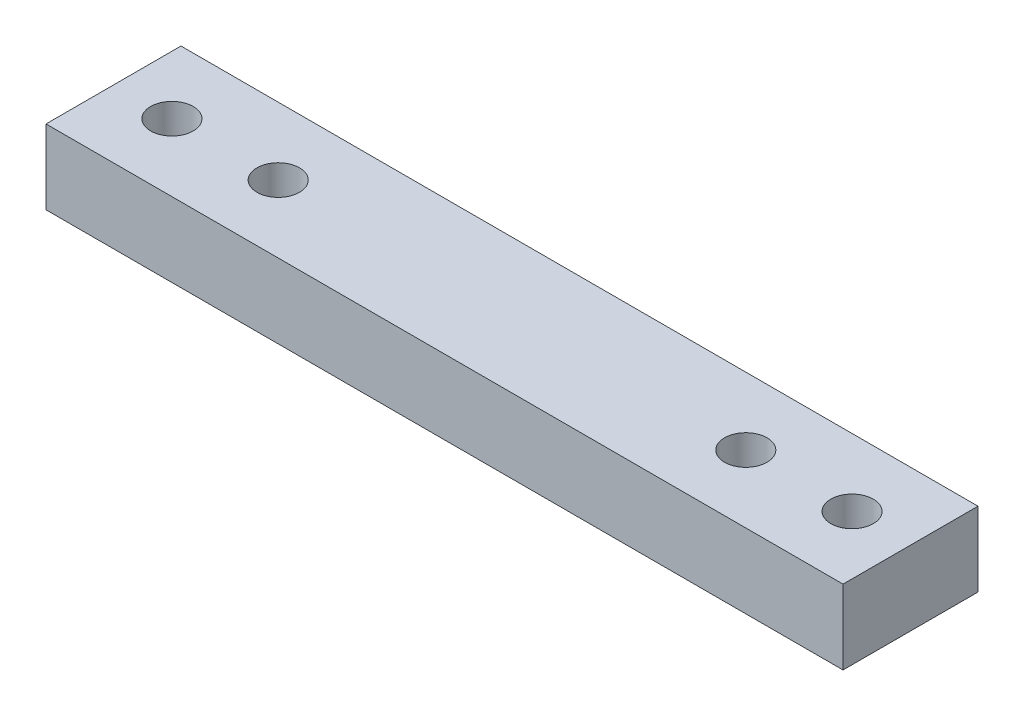
SolidWorks part; units mm, degrees
ref_plane "前视基准面" through (0, 0, 0) normal (0, 0, 1) x (1, 0, 0)
ref_plane "上视基准面" through (0, 0, 0) normal (0, 1, 0) x (1, 0, 0)
ref_plane "右视基准面" through (0, 0, 0) normal (1, 0, 0) x (0, 0, -1)
other "Configuration Table"
sketch "草图1" plane through (0, 0, 0) normal (0, 1, 0) x (1, 0, 0)
  line L1 (-37.5, -6.35) -> (37.5, -6.35)
  line L2 (-37.5, -6.35) -> (-37.5, 6.35)
  line L3 (-37.5, 6.35) -> (37.5, 6.35)
  line L4 (37.5, -6.35) -> (37.5, 6.35)
extrude "Sensor_envelope_75x12p7x7" add sketch "草图1" along normal blind 7
sketch "草图2" plane through (0, 0, 0) normal (0, 1, 0) x (1, 0, 0)
  circle A0 centre (-32, 0) radius 2
  circle A1 centre (-22, 0) radius 2
  circle A2 centre (22, 0) radius 2
  circle A3 centre (32, 0) radius 2
extrude "Four_M4_nominal_holes" cut sketch "草图2" along normal blind 7
